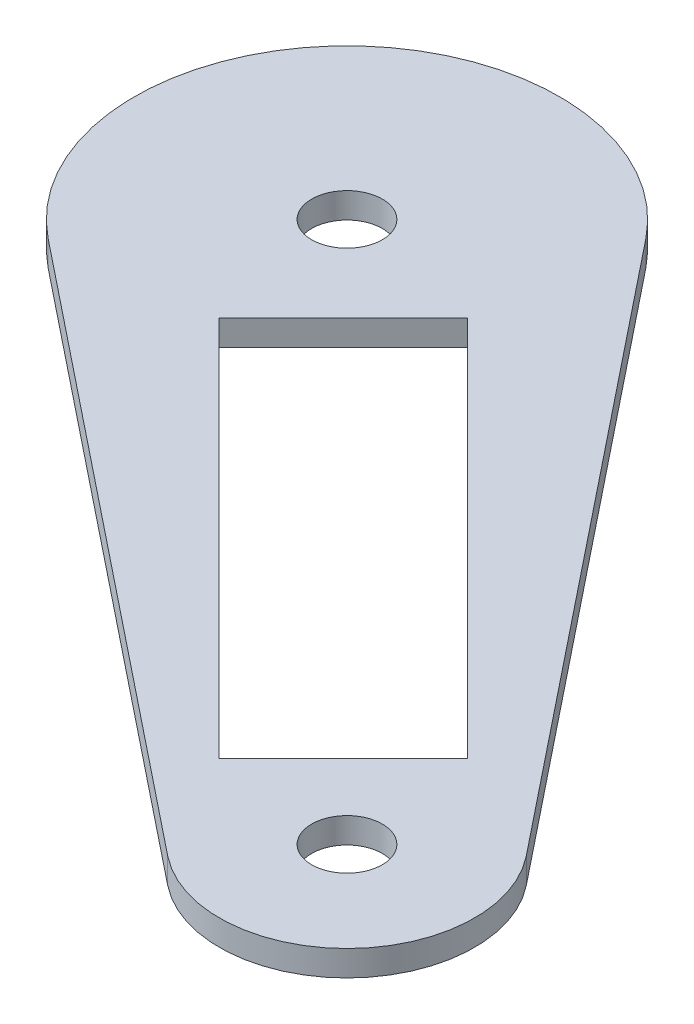
SolidWorks part; units mm, degrees
ref_plane "前视基准面" through (0, 0, 0) normal (0, 0, 1) x (1, 0, 0)
ref_plane "上视基准面" through (0, 0, 0) normal (0, 1, 0) x (1, 0, 0)
ref_plane "右视基准面" through (0, 0, 0) normal (1, 0, 0) x (0, 0, -1)
other "Configuration Table"
sketch "草图1" plane through (0, 0, 0) normal (0, 1, 0) x (1, 0, 0)
  line L0 (-1002.0771, 0) -> (49101.7763, 0) construction
  line L1 (0, -1002.0771) -> (0, 49101.7763) construction
  line L2 (0, 0) -> (63.6396, -63.6396)
  line L3 (19.5324, 15.604) -> (75.359, -54.2772)
  line L4 (-15.604, -19.5324) -> (54.2772, -75.359)
  circle A0 centre (0, 0) radius 4.15
  circle A1 centre (63.6396, -63.6396) radius 4.15
  circle A2 centre (63.6396, -63.6396) radius 15
  circle A3 centre (0, 0) radius 25
  dimension "D2" = 8.3
  dimension "D3" = 8.3
  dimension "D4" = 50
  dimension "D5" = 30
  dimension "D1" = 90
extrude "凸台-拉伸1" add sketch "草图1" along normal blind 3
sketch "草图5" plane through (0, 3, 0) normal (0, 1, 0) x (1, 0, 0)
  line L0 (0, 0) -> (63.6396, -63.6396)
  line L1 (19.5324, 15.604) -> (75.359, -54.2772)
  line L2 (-15.604, -19.5324) -> (54.2772, -75.359)
  line L3 (-14.3557, -17.9698) -> (55.5255, -73.7965)
  line L4 (17.9698, 14.3557) -> (73.7965, -55.5255)
  circle A0 centre (0, 0) radius 25
  circle A1 centre (63.6396, -63.6396) radius 15
  circle A2 centre (0, 0) radius 23
  circle A3 centre (63.6396, -63.6396) radius 13
  line M1 (-15.604, -19.5324) -> (54.2772, -75.359)
  arc M2 (54.2772, -75.359) -> (75.359, -54.2772) centre (63.6396, -63.6396) ccw
  line M3 (75.359, -54.2772) -> (19.5324, 15.604)
  arc M4 (19.5324, 15.604) -> (-15.604, -19.5324) centre (0, 0) ccw
  dimension "D1" = 2
  dimension "D2" = 2
sketch "草图3" plane through (0, 3, 0) normal (0, 1, 0) x (1, 0, 0)
  line L0 (19.5324, 15.604) -> (75.359, -54.2772)
  line L1 (19.5324, 15.604) -> (75.359, -54.2772) construction
  line L2 (-15.604, -19.5324) -> (54.2772, -75.359)
  line L3 (-14.3557, -17.9698) -> (55.5255, -73.7965)
  line L4 (17.9698, 14.3557) -> (73.7965, -55.5255)
  circle A0 centre (0, 0) radius 25
  circle A1 centre (63.6396, -63.6396) radius 15
  circle A2 centre (0, 0) radius 23
  circle A3 centre (63.6396, -63.6396) radius 13
  line M3 (-15.604, -19.5324) -> (54.2772, -75.359)
  arc M4 (54.2772, -75.359) -> (75.359, -54.2772) centre (63.6396, -63.6396) ccw
  line M5 (75.359, -54.2772) -> (19.5324, 15.604)
  arc M6 (19.5324, 15.604) -> (-15.604, -19.5324) centre (0, 0) ccw
  dimension "D1" = 2
  dimension "D2" = 2
extrude "凸台-拉伸2" add sketch "草图3" along normal blind 12 contours A1 L3 A0 M3 | A2 L4 A0 L3 M6 | A1 A0 L4 M5 | A3 L3 A1 L4 M4
sketch "草图4" plane through (0, 3, 0) normal (0, 1, 0) x (1, 0, 0)
  line L0 (0, 0) -> (63.6396, -63.6396)
  line L1 (10.0553, -10.0553) -> (2.5299, -17.5807)
  line L2 (2.5299, -17.5807) -> (47.3842, -62.435)
  line L3 (47.3842, -62.435) -> (54.9096, -54.9096)
  line L4 (54.9096, -54.9096) -> (61.988, -47.8313)
  line L5 (61.988, -47.8313) -> (17.1337, -2.977)
  line L6 (17.1337, -2.977) -> (10.0553, -10.0553)
extrude "切除-拉伸1" cut sketch "草图4" against normal through all contours L5 L6 L0 L4 | L2 L3 L0 L1
extrude "切除-拉伸2" cut sketch "草图5" along normal through all contours A2 L4 A0 L3 M4 | A1 A0 L4 M3 | A1 L3 A0 M1 | A3 L3 A1 L4 M2
